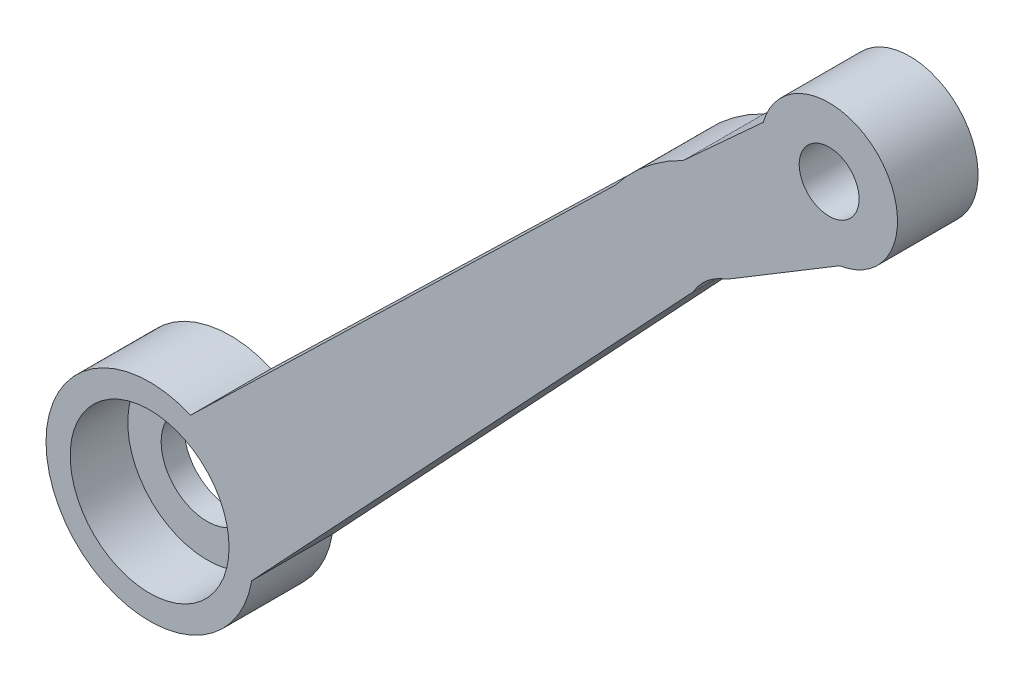
SolidWorks part; units mm, degrees
ref_plane "Front Plane" through (0, 0, 0) normal (0, 0, 1) x (1, 0, 0)
ref_plane "Top Plane" through (0, 0, 0) normal (0, 1, 0) x (1, 0, 0)
ref_plane "Right Plane" through (0, 0, 0) normal (1, 0, 0) x (0, 0, -1)
sketch "Sketch1" plane through (0, 0, 0) normal (0, 0, 1) x (1, 0, 0)
  line L8 (-116.1165, -73.1162) -> (-77.7804, -32.2217)
  line L9 (-74.8335, -29.7976) -> (-65.0583, -23.8962)
  line L10 (-71.6872, -16.4176) -> (-78.6359, -22.7631)
  line L11 (-84.5297, -27.5637) -> (-121.4306, -63.3278)
  circle A0 centre (-65.9692, -18.0264) radius 2.6
  circle A1 centre (-124.987, -71.5953) radius 6.9
  arc A2 (-121.4306, -63.3278) -> (-116.1165, -73.1162) centre (-124.987, -71.5953) ccw
  arc A9 (-74.8335, -29.7976) -> (-77.7804, -32.2217) centre (-73.0977, -34.911) ccw
  arc A10 (-65.0583, -23.8962) -> (-71.6872, -16.4176) centre (-65.9692, -18.0264) ccw
  arc A11 (-78.6359, -22.7631) -> (-84.5297, -27.5637) centre (-71.4001, -37.665) ccw
extrude "Boss-Extrude1" add sketch "Sketch1" along normal blind 5
sketch "Sketch2" plane through (0, 0, 0) normal (0, 0, -1) x (-1, 0, 0)
  line L4 (121.4306, -63.3278) -> (84.5297, -27.5637)
  line L5 (78.6359, -22.7631) -> (71.6872, -16.4176)
  line L6 (65.0583, -23.8962) -> (74.8335, -29.7976)
  line L7 (77.7804, -32.2217) -> (116.1165, -73.1162)
  line L8 (121.4306, -63.3278) -> (84.5297, -27.5637)
  line L9 (78.6359, -22.7631) -> (71.6872, -16.4176)
  line L10 (65.0583, -23.8962) -> (74.8335, -29.7976)
  line L11 (77.7804, -32.2217) -> (116.1165, -73.1162)
  circle A0 centre (124.987, -71.5953) radius 4
  circle A1 centre (65.9692, -18.0264) radius 2.6
  arc A4 (116.1165, -73.1162) -> (121.4306, -63.3278) centre (124.987, -71.5953) ccw
  arc A5 (84.5297, -27.5637) -> (78.6359, -22.7631) centre (71.4001, -37.665) ccw
  arc A6 (71.6872, -16.4176) -> (65.0583, -23.8962) centre (65.9692, -18.0264) ccw
  arc A7 (77.7804, -32.2217) -> (74.8335, -29.7976) centre (73.0977, -34.911) ccw
  arc A8 (116.1165, -73.1162) -> (121.4306, -63.3278) centre (124.987, -71.5953) ccw
  arc A9 (84.5297, -27.5637) -> (78.6359, -22.7631) centre (71.4001, -37.665) ccw
  arc A10 (71.6872, -16.4176) -> (65.0583, -23.8962) centre (65.9692, -18.0264) ccw
  arc A11 (77.7804, -32.2217) -> (74.8335, -29.7976) centre (73.0977, -34.911) ccw
  dimension "D2" = 8
  dimension "D3" = 5.2
  dimension "D1" = 0
extrude "Boss-Extrude2" add sketch "Sketch2" along normal blind 2
scale "Scale1" scale about centroid uniform scaling yes scale factor 1.5
